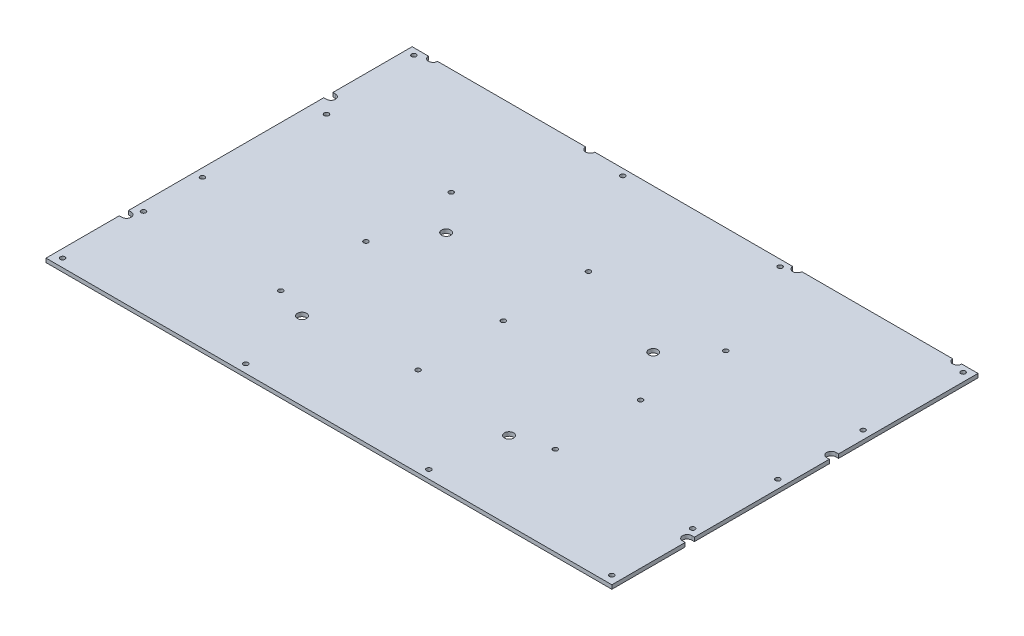
SolidWorks part; units mm, degrees
ref_plane "Front Plane" through (0, 0, 0) normal (0, 0, 1) x (1, 0, 0)
ref_plane "Top Plane" through (0, 0, 0) normal (0, 1, 0) x (1, 0, 0)
ref_plane "Right Plane" through (0, 0, 0) normal (1, 0, 0) x (0, 0, -1)
sketch "Sketch1" plane through (0, 0, 0) normal (0, 1, 0) x (1, 0, 0)
  line L1 (-215.9, -147.35) -> (215.9, -147.35)
  line L2 (-215.9, -147.35) -> (-215.9, 147.35)
  line L3 (-215.9, 147.35) -> (215.9, 147.35)
  line L4 (215.9, -147.35) -> (215.9, 147.35)
  line L5 (-215.9, -147.35) -> (215.9, 147.35) construction
  line L6 (-215.9, 147.35) -> (215.9, -147.35) construction
  point P0 (0, 0)
  dimension "D1" = 294.7
  dimension "D2" = 431.8
extrude "Boss-Extrude1" add sketch "Sketch1" along normal blind 3
sketch "Sketch2" plane through (0, 3, 0) normal (0, 1, 0) x (1, 0, 0)
  line L0 (-215.9, 147.35) -> (-215.9, -147.35) construction
  line L1 (-215.9, -147.35) -> (215.9, -147.35) construction
  line L2 (215.9, 147.35) -> (-215.9, 147.35) construction
  circle A0 centre (-209.55, -125.7) radius 1.775
  circle A1 centre (-209.55, 142.35) radius 1.775
  dimension "D3" = 3.55
  dimension "D5" = 6.35
  dimension "D6" = 3.55
  dimension "D1" = 6.35
  dimension "D2" = 21.65
  dimension "D4" = 5
extrude "Cut-Extrude1" cut sketch "Sketch2" against normal through all
pattern_linear "LPattern1" count 4 spacing 139.7 along (1, 0, 0) of "Cut-Extrude1"
sketch "Sketch3" plane through (0, 3, 0) normal (0, 1, 0) x (1, 0, 0)
  line L0 (-209.55, -64) -> (-209.55, -125.7) construction
  line L1 (215.9, 147.35) -> (-215.9, 147.35) construction
  circle A0 centre (-209.55, -64) radius 1.775
  dimension "D2" = 3.55
  dimension "D1" = 211.35
extrude "Cut-Extrude2" cut sketch "Sketch3" against normal through all
pattern_linear "LPattern2" count 5 spacing 104.77 along (1, 0, 0) count 3 spacing 65 along (0, 0, -1) skipping (0, 1), (0, 2) of "Cut-Extrude2"
sketch "Sketch4" plane through (0, 3, 0) normal (0, 1, 0) x (1, 0, 0)
  line L0 (-209.55, -19) -> (-209.55, -64) construction
  line L1 (-215.9, 147.35) -> (-215.9, -147.35) construction
  circle A0 centre (-203.9, 70) radius 1.775
  circle A2 centre (-104.78, 66) radius 1.775 construction
  circle A3 centre (-209.55, -64) radius 1.775 construction
  circle A4 centre (-209.55, -19) radius 1.775
  dimension "D1" = 4
  dimension "D2" = 45
  dimension "D3" = 12
extrude "Cut-Extrude3" cut sketch "Sketch4" against normal blind 10
sketch "Sketch7" plane through (0, 0, 0) normal (0, -1, 0) x (1, 0, 0)
  circle A0 centre (-213.9, -83.38) radius 3.5
  circle A1 centre (-213.9, 72.58) radius 3.5
  circle A2 centre (-200, 140.04) radius 3.5 construction
  circle A3 centre (-80, 140.04) radius 3.5 construction
  circle A4 centre (78, 140.04) radius 3.5 construction
  circle A5 centre (200, 140.04) radius 3.5 construction
  circle A6 centre (213.9, 72.58) radius 3.5
  circle A7 centre (213.9, -37.42) radius 3.5
  circle A8 centre (200, -147.42) radius 3.5
  circle A9 centre (78, -147.42) radius 3.5
  circle A10 centre (-80, -147.42) radius 3.5
  circle A11 centre (-80, -37.42) radius 3.5
  circle A12 centre (78, -37.42) radius 3.5
  circle A13 centre (78, 72.58) radius 3.5
  circle A14 centre (-80, 72.58) radius 3.5
  circle A15 centre (-200, -147.42) radius 3.5
  dimension "D1" = 7
extrude "Cut-Extrude5" cut sketch "Sketch7" against normal through all
sketch "Sketch8" plane through (0, 3, 0) normal (0, 1, 0) x (1, 0, 0)
  line L0 (215.9, 40.2923) -> (215.9, 147.35) construction
  line L1 (213.9, 33.92) -> (215.9, 33.92)
  line L2 (213.9, 33.92) -> (213.9, 40.92)
  line L3 (213.9, 40.92) -> (215.9, 40.92)
  line L4 (215.9, 33.92) -> (215.9, 40.92)
  line L5 (215.9, -69.7077) -> (215.9, 34.5477) construction
  line L6 (213.9, -69.08) -> (215.9, -69.08)
  line L7 (213.9, -69.08) -> (213.9, -76.08)
  line L8 (213.9, -76.08) -> (215.9, -76.08)
  line L9 (215.9, -69.08) -> (215.9, -76.08)
  line L10 (-215.9, 80.5077) -> (-215.9, -69.7077) construction
  line L11 (-213.9, 86.88) -> (-215.9, 86.88)
  line L12 (-213.9, 86.88) -> (-213.9, 79.88)
  line L13 (-213.9, 79.88) -> (-215.9, 79.88)
  line L14 (-215.9, 86.88) -> (-215.9, 79.88)
  line L15 (-215.9, -75.4523) -> (-215.9, -147.35) construction
  line L16 (-213.9, -69.08) -> (-215.9, -69.08)
  line L17 (-213.9, -69.08) -> (-213.9, -76.08)
  line L18 (-213.9, -76.08) -> (-215.9, -76.08)
  line L19 (-215.9, -69.08) -> (-215.9, -76.08)
  arc A0 (215.9, 40.2923) -> (215.9, 34.5477) centre (213.9, 37.42) ccw construction
  arc A1 (215.9, -69.7077) -> (215.9, -75.4523) centre (213.9, -72.58) ccw construction
  arc A2 (-215.9, 80.5077) -> (-215.9, 86.2523) centre (-213.9, 83.38) ccw construction
  arc A3 (-215.9, -75.4523) -> (-215.9, -69.7077) centre (-213.9, -72.58) ccw construction
extrude "Cut-Extrude6" cut sketch "Sketch8" against normal through all
sketch "Sketch9" plane through (0, 0, 0) normal (0, -1, 0) x (1, 0, 0)
  line L0 (-215.9, 76.08) -> (-215.9, 147.35) construction
  line L1 (215.9, 147.35) -> (-215.9, 147.35)
  line L2 (215.9, 147.35) -> (215.9, 132.05)
  line L3 (215.9, 132.05) -> (-215.9, 132.05)
  line L4 (-215.9, 147.35) -> (-215.9, 132.05)
  dimension "D1" = 15.3
extrude "Cut-Extrude7" cut sketch "Sketch9" against normal through all
sketch "Sketch11" plane through (0, 3, 0) normal (0, 1, 0) x (1, 0, 0)
  circle A0 centre (-69.85, 142.35) radius 1.775 construction
  circle A1 centre (-69.85, 142.35) radius 1.775
extrude "Boss-Extrude3" add sketch "Sketch11" against normal up to surface (3 mm away) up to face at (-0.1429, 0, -39.2229)
sketch "Sketch12" plane through (0, 3, 0) normal (0, 1, 0) x (1, 0, 0)
  line L0 (-50.15, 142.35) -> (69.85, 142.35) construction
  circle A0 centre (-50.15, 142.35) radius 1.775
  circle A1 centre (69.85, 142.35) radius 1.775 construction
  dimension "D1" = 120
extrude "Cut-Extrude8" cut sketch "Sketch12" against normal through all
